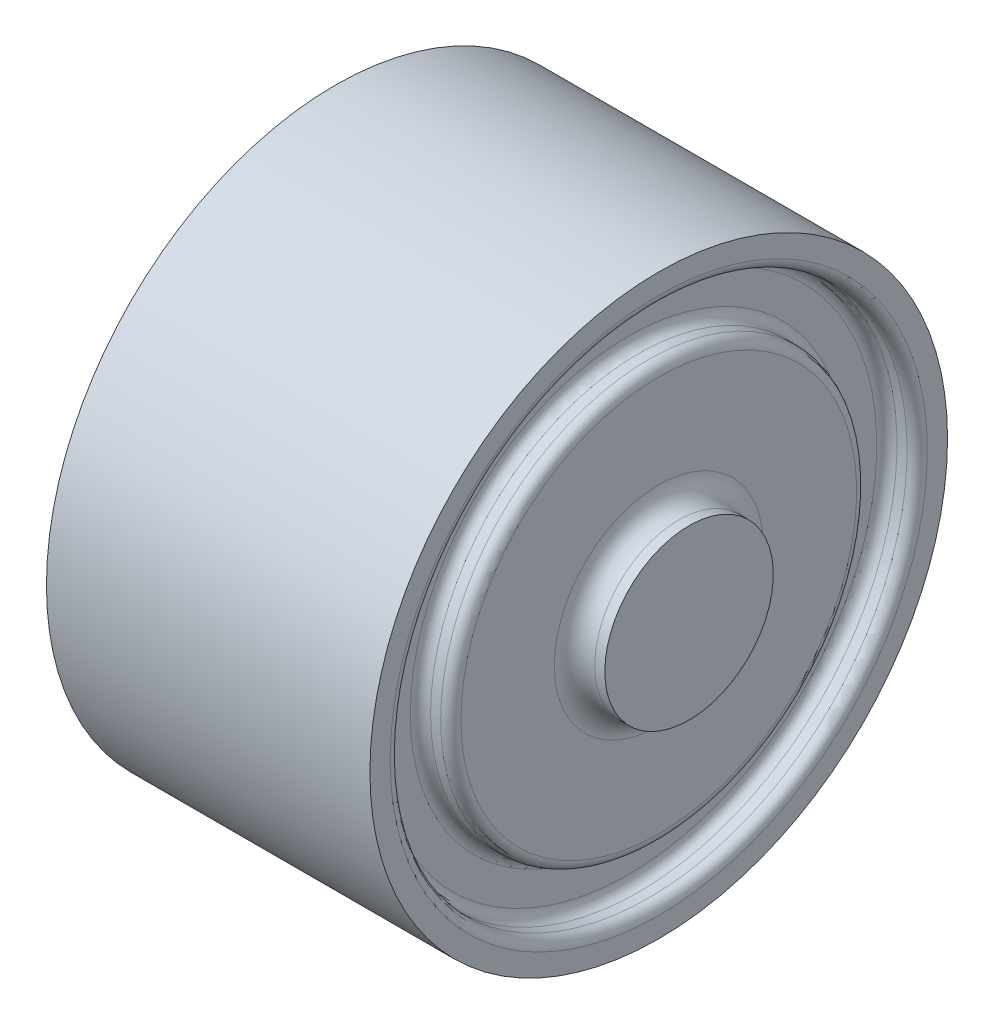
SolidWorks part; units mm, degrees
ref_plane "前视基准面" through (0, 0, 0) normal (0, 0, 1) x (1, 0, 0)
ref_plane "上视基准面" through (0, 0, 0) normal (0, 1, 0) x (1, 0, 0)
ref_plane "右视基准面" through (0, 0, 0) normal (1, 0, 0) x (0, 0, -1)
ref_plane "基准面4" through (0, 0, 0) normal (0, 0, 1) x (1, 0, 0)
sketch "草图1" plane through (0, 0, 0) normal (0, 0, 1) x (1, 0, 0)
  line L0 (-19, 0) -> (-19, 8.3333)
  line L1 (-19, 8.3333) -> (-18, 8.3333)
  line L2 (-16, 10.3333) -> (-16, 19.5714)
  line L3 (-15, 20.5714) -> (-14, 20.5714)
  line L4 (-13, 21.5714) -> (-13, 24.5714)
  line L5 (-14, 25.5714) -> (-15, 25.5714)
  line L6 (-16, 26.5714) -> (-16, 28.5714)
  line L7 (-16, 28.5714) -> (16, 28.5714)
  line L8 (16, 28.5714) -> (16, 26.5714)
  line L9 (15, 25.5714) -> (14, 25.5714)
  line L10 (13, 24.5714) -> (13, 21.5714)
  line L11 (14, 20.5714) -> (15, 20.5714)
  line L12 (16, 19.5714) -> (16, 10.3333)
  line L13 (18, 8.3333) -> (19, 8.3333)
  line L14 (19, 8.3333) -> (19, 0)
  line L15 (19, 0) -> (-19, 0)
  line L16 (19, 0) -> (-19, 0) construction
  arc A0 (-18, 8.3333) -> (-16, 10.3333) centre (-18, 10.3333) ccw
  arc A1 (-16, 19.5714) -> (-15, 20.5714) centre (-15, 19.5714) cw
  arc A2 (-14, 20.5714) -> (-13, 21.5714) centre (-14, 21.5714) ccw
  arc A3 (-13, 24.5714) -> (-14, 25.5714) centre (-14, 24.5714) ccw
  arc A4 (-15, 25.5714) -> (-16, 26.5714) centre (-15, 26.5714) cw
  arc A5 (16, 26.5714) -> (15, 25.5714) centre (15, 26.5714) cw
  arc A6 (14, 25.5714) -> (13, 24.5714) centre (14, 24.5714) ccw
  arc A7 (13, 21.5714) -> (14, 20.5714) centre (14, 21.5714) ccw
  arc A8 (15, 20.5714) -> (16, 19.5714) centre (15, 19.5714) cw
  arc A9 (16, 10.3333) -> (18, 8.3333) centre (18, 10.3333) ccw
revolve "旋转1" add sketch "草图1" angle 360 about L16
